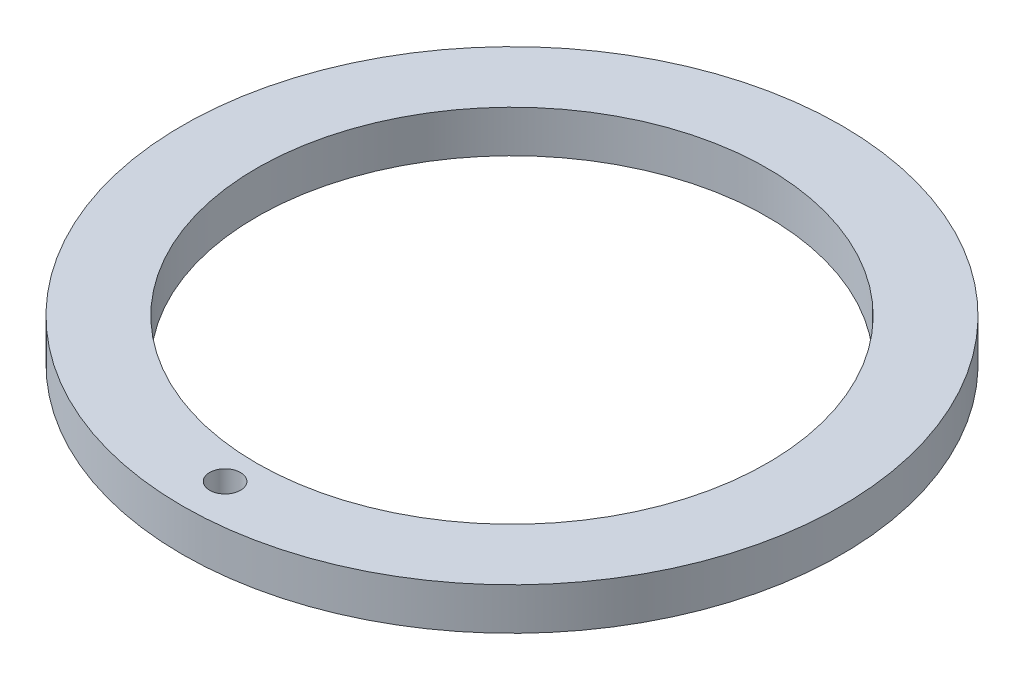
SolidWorks part; units mm, degrees
material "C-Glass Fiber"
ref_plane "Front Plane" through (0, 0, 0) normal (0, 0, 1) x (1, 0, 0)
ref_plane "Top Plane" through (0, 0, 0) normal (0, 1, 0) x (1, 0, 0)
ref_plane "Right Plane" through (0, 0, 0) normal (1, 0, 0) x (0, 0, -1)
sketch "Sketch1" plane through (0, 0, 0) normal (0, 1, 0) x (1, 0, 0)
  circle A0 centre (0, 0) radius 39.37
  circle A1 centre (0, 0) radius 50.8
  dimension "D1" = 101.6
  dimension "D2" = 78.74
extrude "Boss-Extrude2" add sketch "Sketch1" along normal blind 6.477 contours A1 | A0
sketch "Sketch2" plane through (0, 0, 0) normal (0, 1, 0) x (1, 0, 0)
  line L0 (0, 0) -> (0, -57.6428) construction
  circle A0 centre (0, -44.2277) radius 2.3812
  circle A1 centre (0, 0) radius 39.37 construction
  dimension "D1" = 4.7625
  dimension "D2" = 44.2277
extrude "Cut-Extrude1" cut sketch "Sketch2" along normal through all
